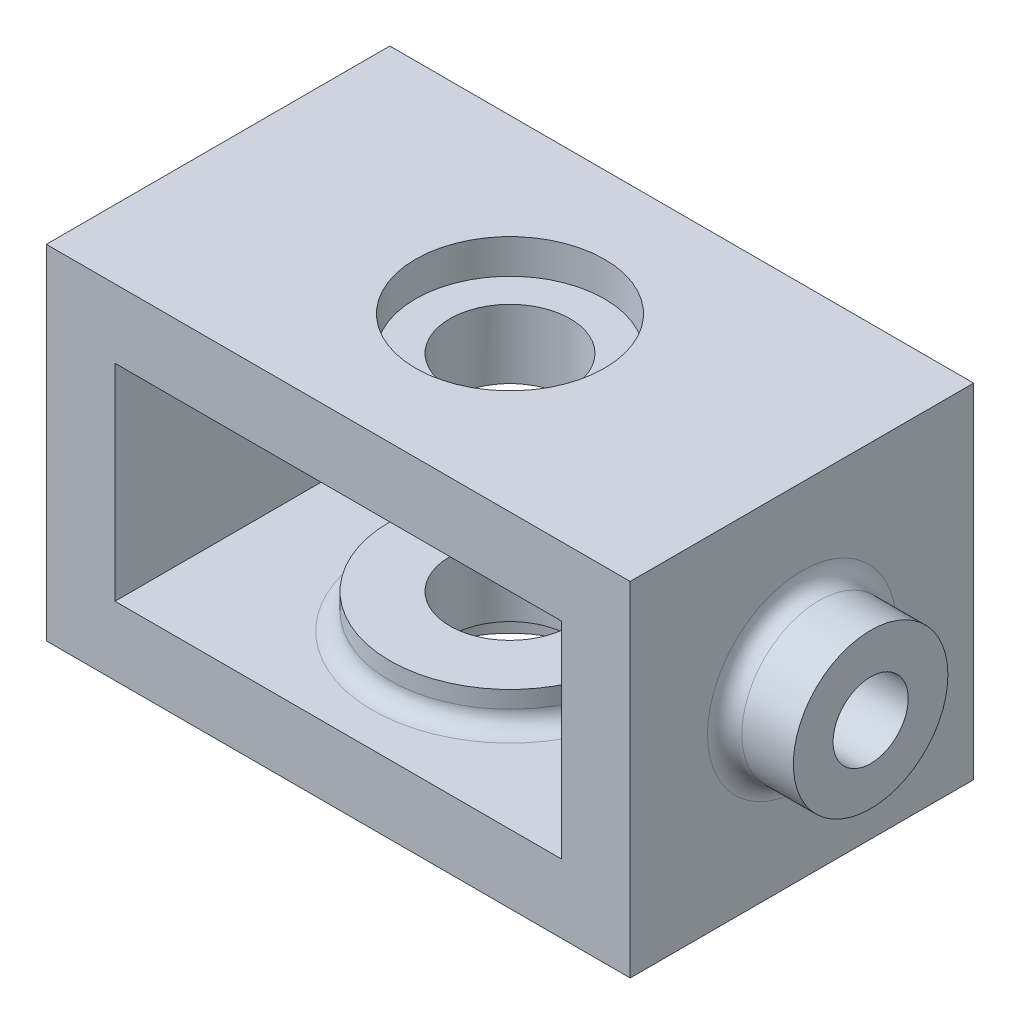
SolidWorks part; units mm, degrees
ref_plane "Front Plane" through (0, 0, 0) normal (0, 0, 1) x (1, 0, 0)
ref_plane "Top Plane" through (0, 0, 0) normal (0, 1, 0) x (1, 0, 0)
ref_plane "Right Plane" through (0, 0, 0) normal (1, 0, 0) x (0, 0, -1)
sketch "Sketch1" plane through (0, 0, 0) normal (0, 0, 1) x (1, 0, 0)
  line L1 (-86.36, 50.8) -> (0, 50.8)
  line L2 (-86.36, 50.8) -> (-86.36, 0)
  line L3 (-86.36, 0) -> (0, 0)
  line L4 (0, 50.8) -> (0, 0)
  line L5 (-86.36, 50.8) -> (0, 0) construction
  line L6 (-86.36, 0) -> (0, 50.8) construction
  point P0 (-43.18, 25.4)
  point P5 (0, 0)
  dimension "D1" = 86.36
  dimension "D2" = 50.8
extrude "Boss-Extrude1" add sketch "Sketch1" along normal blind 50.8 contours L2 L1 L4 L3
sketch "Sketch2" plane through (0, 0, 0) normal (1, 0, 0) x (0, 0, -1)
  line L0 (0, 50.8) -> (0, 0) construction
  line L1 (-50.8, 50.8) -> (0, 50.8) construction
  circle A0 centre (-25.4, 25.4) radius 11.43
  circle A1 centre (-25.4, 25.4) radius 5.5562
  dimension "D1" = 22.86
  dimension "D2" = 11.1125
  dimension "D3" = 25.4
  dimension "D4" = 25.4
extrude "Cut-Extrude1" cut sketch "Sketch2" against normal through all contours A1
sketch "Sketch10" plane through (0, 0, 0) normal (1, 0, 0) x (0, 0, -1)
  line L0 (0, 50.8) -> (0, 0) construction
  line L1 (-50.8, 0) -> (0, 0) construction
  circle A0 centre (-25.4, 25.4941) radius 11.43
  point P4 (0, 0)
  dimension "D3" = 22.86
  dimension "D1" = 25.4
  dimension "D2" = 25.4941
extrude "Boss-Extrude3" add sketch "Sketch10" along normal blind 10.16
sketch "Sketch11" plane through (10.16, 0, 0) normal (1, 0, 0) x (0, 0, -1)
  line L0 (0, 50.8) -> (0, 0) construction
  line L1 (-50.8, 0) -> (0, 0) construction
  circle A0 centre (-25.4, 25.4) radius 5.5562
  dimension "D3" = 11.1125
  dimension "D1" = 25.4
  dimension "D2" = 25.4
extrude "Cut-Extrude2" cut sketch "Sketch11" against normal through all
sketch "Sketch12" plane through (-86.36, 0, 0) normal (-1, 0, 0) x (0, 0, 1)
  line L0 (0, 50.8) -> (0, 0) construction
  line L1 (50.8, 0) -> (0, 0) construction
  circle A0 centre (25.4, 25.4) radius 11.43
  dimension "D1" = 22.86
  dimension "D2" = 25.4
  dimension "D3" = 25.4
extrude "Boss-Extrude4" add sketch "Sketch12" along normal blind 10.16
sketch "Sketch13" plane through (-96.52, 0, 0) normal (-1, 0, 0) x (0, 0, 1)
  line L0 (50.8, 50.8) -> (50.8, 0) construction
  line L2 (50.8, 0) -> (0, 0) construction
  circle A0 centre (25.4, 25.4) radius 5.5562
  dimension "D3" = 11.1125
  dimension "D1" = 25.4
  dimension "D2" = 25.4
extrude "Cut-Extrude3" cut sketch "Sketch13" against normal through all contours A0
sketch "Sketch14" plane through (0, 0, 50.8) normal (0, 0, 1) x (1, 0, 0)
  line L0 (0, 50.8) -> (0, 0) construction
  line L1 (-76.2, 40.64) -> (-10.16, 40.64)
  line L2 (-76.2, 40.64) -> (-76.2, 10.16)
  line L3 (-76.2, 10.16) -> (-10.16, 10.16)
  line L4 (-10.16, 40.64) -> (-10.16, 10.16)
  line L5 (-76.2, 40.64) -> (-10.16, 10.16) construction
  line L6 (-76.2, 10.16) -> (-10.16, 40.64) construction
  line L7 (-86.36, 0) -> (0, 0) construction
  line L9 (-86.36, 50.8) -> (0, 50.8) construction
  line L10 (-86.36, 50.8) -> (-86.36, 0) construction
  point P0 (-43.18, 25.4)
  dimension "D1" = 10.16
  dimension "D2" = 10.16
  dimension "D3" = 10.16
  dimension "D4" = 10.16
extrude "Cut-Extrude4" cut sketch "Sketch14" against normal through all contours L2 L1 L4 L3
sketch "Sketch15" plane through (0, 50.8, 0) normal (0, 1, 0) x (1, 0, 0)
  line L0 (-86.36, -50.8) -> (0, -50.8) construction
  circle A0 centre (-43.18, -25.4) radius 13.97
  dimension "D1" = 27.94
  dimension "D2" = 43.18
  dimension "D3" = 25.4
extrude "Cut-Extrude5" cut sketch "Sketch15" against normal blind 5.08 contours A0
sketch "Sketch16" plane through (0, 45.72, 0) normal (0, 1, 0) x (1, 0, 0)
  line L0 (0, -50.8) -> (0, 0) construction
  line L3 (-86.36, -50.8) -> (0, -50.8) construction
  circle A0 centre (-43.18, -25.4) radius 8.89
  dimension "D1" = 17.78
  dimension "D2" = 43.18
  dimension "D3" = 25.4
extrude "Cut-Extrude6" cut sketch "Sketch16" against normal through all contours A0
sketch "Sketch17" plane through (0, 0, 0) normal (0, -1, 0) x (1, 0, 0)
  circle A0 centre (-43.18, 25.4) radius 13.97
  dimension "D1" = 27.94
extrude "Cut-Extrude7" cut sketch "Sketch17" against normal blind 5.08
sketch "Sketch18" plane through (0, 10.16, 0) normal (0, 1, 0) x (1, 0, 0)
  line L0 (0, -50.8) -> (0, 0) construction
  line L1 (-76.2, 0) -> (-10.16, 0) construction
  circle A0 centre (-43.18, -25.4) radius 17.78
  dimension "D3" = 35.56
  dimension "D1" = 43.18
  dimension "D2" = 25.4
extrude "Boss-Extrude5" add sketch "Sketch18" along normal blind 5.08
sketch "Sketch19" plane through (0, 40.64, 0) normal (0, -1, 0) x (1, 0, 0)
  circle A0 centre (-43.18, 25.4) radius 17.78
  dimension "D1" = 35.56
extrude "Boss-Extrude6" add sketch "Sketch19" along normal blind 5.08
sketch "Sketch21" plane through (0, 10.16, 0) normal (0, -1, 0) x (-1, 0, 0)
  line L0 (0, -50.8) -> (0, 0) construction
  line L1 (86.36, 0) -> (0, 0) construction
  circle A0 centre (43.18, -25.4) radius 8.89
  dimension "D1" = 17.78
  dimension "D2" = 43.18
  dimension "D3" = 25.4
extrude "Cut-Extrude8" cut sketch "Sketch21" against normal through all
fillet "Fillet1" radius 2.54 4 edges at (-86.36, 25.4, 13.97) (-43.18, 40.64, 7.62) (0, 25.4941, 13.97) (-25.4, 10.16, 25.4)
